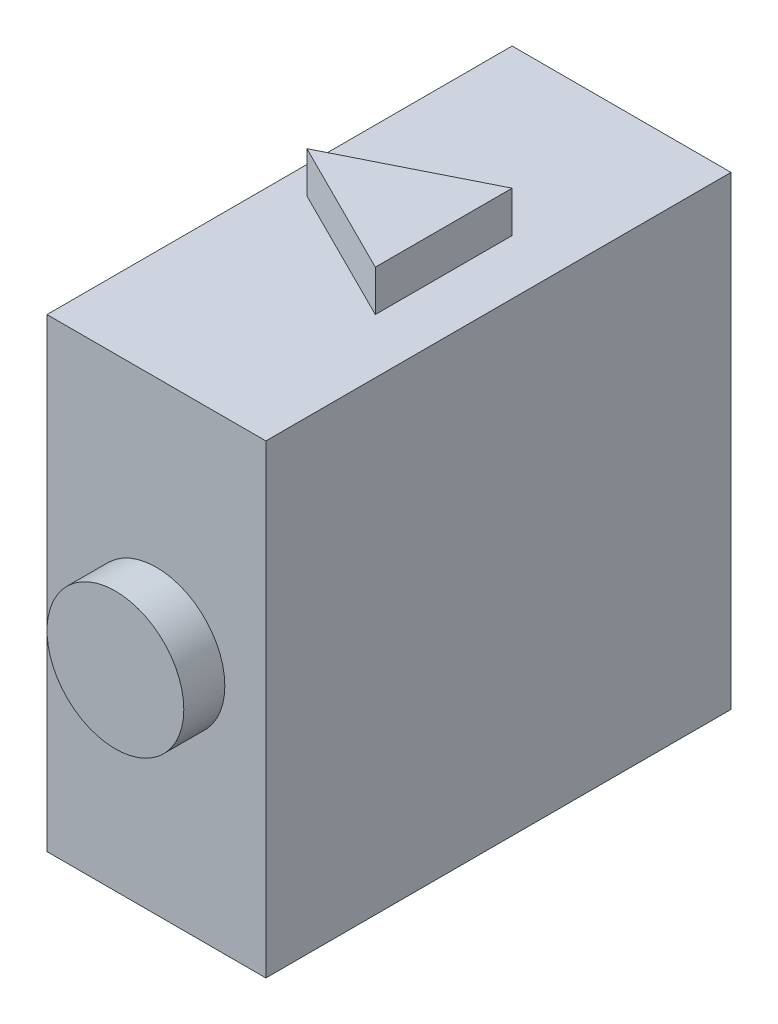
SolidWorks part; units mm, degrees
material "ABS"
ref_plane "Front Plane" through (0, 0, 0) normal (0, 0, 1) x (1, 0, 0)
ref_plane "Top Plane" through (0, 0, 0) normal (0, 1, 0) x (1, 0, 0)
ref_plane "Right Plane" through (0, 0, 0) normal (1, 0, 0) x (0, 0, -1)
ref_plane "Y+23_000" through (0, 23, 0) normal (0, 1, 0) x (1, 0, 0)
sketch "Sketch1" plane through (0, 23, 0) normal (0, 1, 0) x (1, 0, 0)
  line L1 (-8, -17) -> (8, -17)
  line L2 (-8, -17) -> (-8, 17)
  line L3 (-8, 17) -> (8, 17)
  line L4 (8, -17) -> (8, 17)
extrude "Boss-Extrude1" add sketch "Sketch1" along normal mid plane 34
ref_plane "X-5_000" through (-5, 0, 0) normal (1, 0, 0) x (0, 0, -1)
sketch "Sketch2" plane through (-5, 0, 0) normal (1, 0, 0) x (0, 0, -1)
  line L1 (-12, 10) -> (12, 10)
  line L2 (-12, 10) -> (-12, 36)
  line L3 (-12, 36) -> (12, 36)
  line L4 (12, 10) -> (12, 36)
extrude "Cut-Extrude1" cut sketch "Sketch2" against normal mid plane 6
ref_plane "Z+18_500" through (0, 0, 18.5) normal (0, 0, 1) x (1, 0, 0)
sketch "Sketch3" plane through (0, 0, 18.5) normal (0, 0, 1) x (1, 0, 0)
  line L0 (8.8, 23) -> (-8.8, 23) construction
  circle A0 centre (0, 23) radius 5
extrude "Boss-Extrude2" add sketch "Sketch3" along normal mid plane 3
ref_plane "Y+41_500" through (0, 41.5, 0) normal (0, 1, 0) x (1, 0, 0)
sketch "Sketch4" plane through (0, 41.5, 0) normal (0, 1, 0) x (1, 0, 0)
  line L0 (4, 5) -> (4, -5)
  line L1 (4, -5) -> (-6, 0)
  line L2 (-6, 0) -> (4, 5)
extrude "Boss-Extrude3" add sketch "Sketch4" along normal mid plane 3
